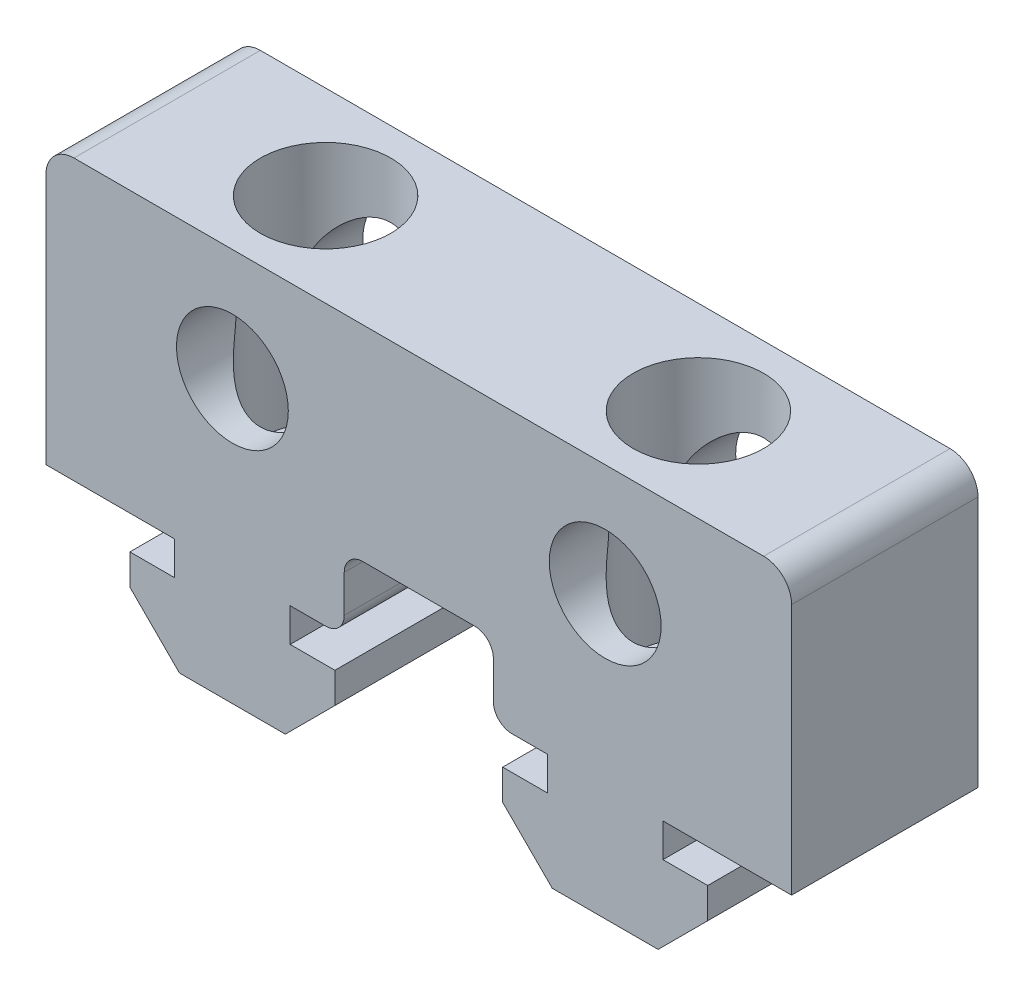
SolidWorks part; units mm, degrees
ref_plane "前视基准面" through (0, 0, 0) normal (0, 0, 1) x (1, 0, 0)
ref_plane "上视基准面" through (0, 0, 0) normal (0, 1, 0) x (1, 0, 0)
ref_plane "右视基准面" through (0, 0, 0) normal (1, 0, 0) x (0, 0, -1)
sketch "草图1" plane through (0, 0, 0) normal (0, 0, 1) x (1, 0, 0)
  line L0 (-20, 0) -> (20, 0)
  line L5 (-20, 0) -> (-20, 15)
  line L6 (-20, 15) -> (20, 15)
  line L7 (20, 15) -> (20, 0)
  circle A0 centre (-10, 9) radius 3
  circle A1 centre (10, 9) radius 3
  point P0 (0, 0)
extrude "凸台-拉伸1" add sketch "草图1" along normal blind 10
sketch "草图4" plane through (0, 0, 10) normal (0, 0, 1) x (1, 0, 0)
  line L4 (-6.9, -1.8) -> (-6.9, 0)
  line L5 (-13.1, -1.8) -> (-13.1, 0)
  line L6 (-4.5, -3.4393) -> (-4.5, -1.8)
  line L7 (-4.5, -3.4393) -> (-7.1607, -6.1)
  line L10 (-13.1, -1.8) -> (-15.5, -1.8)
  line L14 (-12.8393, -6.1) -> (-7.1607, -6.1)
  line L18 (-6.9, -1.8) -> (-4.5, -1.8)
  line L20 (-15.5, -3.4393) -> (-12.8393, -6.1)
  line L21 (-15.5, -3.4393) -> (-15.5, -1.8)
  line L42 (13.1, -1.8) -> (13.1, 0)
  line L43 (6.9, -1.8) -> (6.9, 0)
  line L46 (15.5, -3.4393) -> (15.5, -1.8)
  line L47 (15.5, -3.4393) -> (12.8393, -6.1)
  line L49 (6.9, -1.8) -> (4.5, -1.8)
  line L53 (7.1607, -6.1) -> (12.8393, -6.1)
  line L55 (13.1, -1.8) -> (15.5, -1.8)
  line L58 (4.5, -3.4393) -> (7.1607, -6.1)
  line L59 (4.5, -3.4393) -> (4.5, -1.8)
  line L86 (-13.1, 0) -> (-6.9, 0)
  line L87 (6.9, 0) -> (13.1, 0)
  point P8 (-10, -1.8)
  point P9 (-9.8043, -1.8)
  point P13 (-10, -1.8)
  point P20 (-5, -5)
  point P33 (-15, -5)
  point P58 (10, -1.8)
  point P59 (10.1957, -1.8)
  point P63 (10, -1.8)
  point P70 (15, -5)
  point P83 (5, -5)
extrude "凸台-拉伸2" add sketch "草图4" against normal blind 10
fillet "圆角1" radius 1.5 2 edges at (20, 15, 5) (-20, 15, 5)
sketch "草图5" plane through (0, 15, 0) normal (0, 1, 0) x (1, 0, 0)
  circle A0 centre (-10, -5) radius 3.5
  circle A1 centre (10, -5) radius 3.5
extrude "切除-拉伸1" cut sketch "草图5" against normal blind 13
sketch "草图6" plane through (0, 2, 0) normal (0, 1, 0) x (1, 0, 0)
  circle A0 centre (10, -5) radius 1.75
  circle A1 centre (-10, -5) radius 1.75
extrude "切除-拉伸2" cut sketch "草图6" against normal blind 13
sketch "草图7" plane through (0, 0, 10) normal (0, 0, 1) x (1, 0, 0)
  line L1 (-6.9, 0) -> (6.9, 0) construction
  line L2 (0, 4) -> (-4, 4)
  line L3 (-4, 4) -> (-4, 0)
  line L4 (-4, 0) -> (4, 0)
  line L5 (4, 0) -> (4, 4)
  line L6 (4, 4) -> (0, 4)
extrude "切除-拉伸3" cut sketch "草图7" against normal blind 13
fillet "圆角2" radius 1 4 edges at (-4, 0, 5) (4, 0, 5) (4, 4, 5) (-4, 4, 5)
